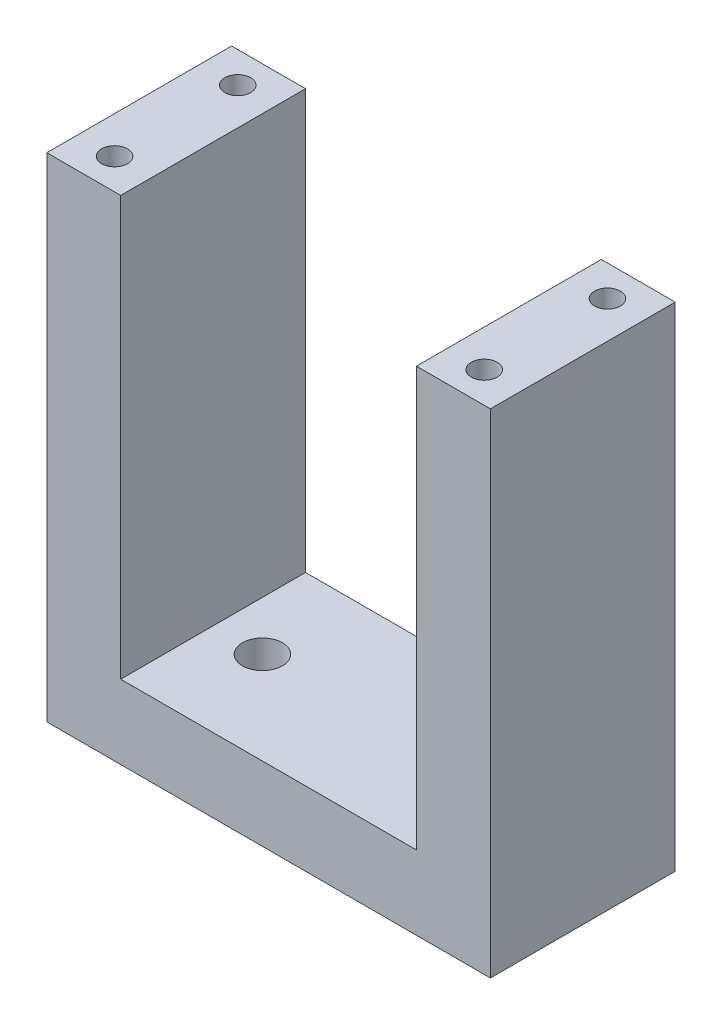
SolidWorks part; units mm, degrees
ref_plane "前视基准面" through (0, 0, 0) normal (0, 0, 1) x (1, 0, 0)
ref_plane "上视基准面" through (0, 0, 0) normal (0, 1, 0) x (1, 0, 0)
ref_plane "右视基准面" through (0, 0, 0) normal (1, 0, 0) x (0, 0, -1)
sketch "草图1" plane through (0, 0, 0) normal (0, 0, 1) x (1, 0, 0)
  line L0 (-36, 80) -> (-36, 0)
  line L1 (-36, 0) -> (36, 0)
  line L2 (36, 0) -> (36, 80)
  line L3 (-24, 80) -> (-24, 12)
  line L4 (-24, 12) -> (24, 12)
  line L5 (24, 12) -> (24, 80)
  line L6 (-36, 80) -> (-24, 80)
  line L7 (24, 80) -> (36, 80)
  dimension "D2" = 72
  dimension "D3" = 12
  dimension "D4" = 80
  dimension "D1" = 12
extrude "凸台-拉伸1" add sketch "草图1" along normal mid plane 30
hole_wizard "M5x0.8 螺纹孔1" positions "草图3" profile "草图2" tap size "M5x0.8" standard "JIS"
sketch "草图3" plane through (0, 80, 0) normal (0, 1, 0) x (-1, 0, 0)
  line L0 (0, 0) -> (0, -21.3119) construction
  line L2 (0, 0) -> (47.5685, 0) construction
  point P0 (-30, -10)
  point P1 (30, -10)
  point P3 (30, 10)
  point P5 (-30, 10)
  dimension "D1" = 60
  dimension "D2" = 20
sketch "草图2" plane through (30, 80, -10) normal (1, 0, 0) x (0, 0, 1)
  line L0 (0, 0) -> (0, 13.6618)
  line L1 (0, 13.6618) -> (2.1, 12.4)
  line L2 (2.1, 12.4) -> (2.1, 0)
  line L5 (2.1, 0) -> (0, 0)
  line L10 (0, 13.6618) -> (-2.1, 12.4) construction
  line L11 (0, -6.35) -> (0, 107.95) construction
  dimension "螺纹孔钻头直径" = 4.2
  dimension "螺纹孔钻头深度" = 12.4
  dimension "导头角度" = 118
cosmetic thread "孔螺蚊线1" parameters "D1"=10, "D2"=5
cosmetic thread "孔螺蚊线2" parameters "D1"=10, "D2"=5
cosmetic thread "孔螺蚊线3" parameters "D1"=10, "D2"=5
cosmetic thread "孔螺蚊线4" parameters "D1"=10, "D2"=5
sketch "草图4" plane through (0, 12, 0) normal (0, 1, 0) x (1, 0, 0)
  line L0 (0, 0) -> (0, 21.9208) construction
  line L1 (0, 0) -> (20.4459, 0) construction
  line L2 (24, 15) -> (-24, 15) construction
  circle A0 centre (-16, 0) radius 3.25
  circle A1 centre (16, 0) radius 3.25
  dimension "D3" = 6.5
  dimension "D1" = 32
  dimension "D2" = 15
extrude "切除-拉伸1" cut sketch "草图4" against normal through all
sketch "草图5" plane through (0, 0, 15) normal (0, 0, 1) x (1, 0, 0)
  line L0 (24, 12) -> (-24, 12) construction
  line L1 (-14.5, 12) -> (-8.5, 12)
  line L2 (-14.5, 12) -> (-14.5, 0)
  line L3 (-14.5, 0) -> (-8.5, 0)
  line L4 (-8.5, 12) -> (-8.5, 0)
  line L5 (0, 0) -> (0, 22.8279) construction
  line L6 (-36, 0) -> (36, 0) construction
  line L7 (8.5, 12) -> (8.5, 0)
  line L8 (14.5, 0) -> (8.5, 0)
  line L9 (14.5, 12) -> (14.5, 0)
  line L10 (14.5, 12) -> (8.5, 12)
  line L11 (-11.5, 12) -> (-11.5, 0) construction
  line L12 (11.5, 12) -> (11.5, 0) construction
  dimension "D1" = 23
  dimension "D2" = 6
extrude "切除-拉伸2" [suppressed] cut sketch "草图5" against normal blind 7
